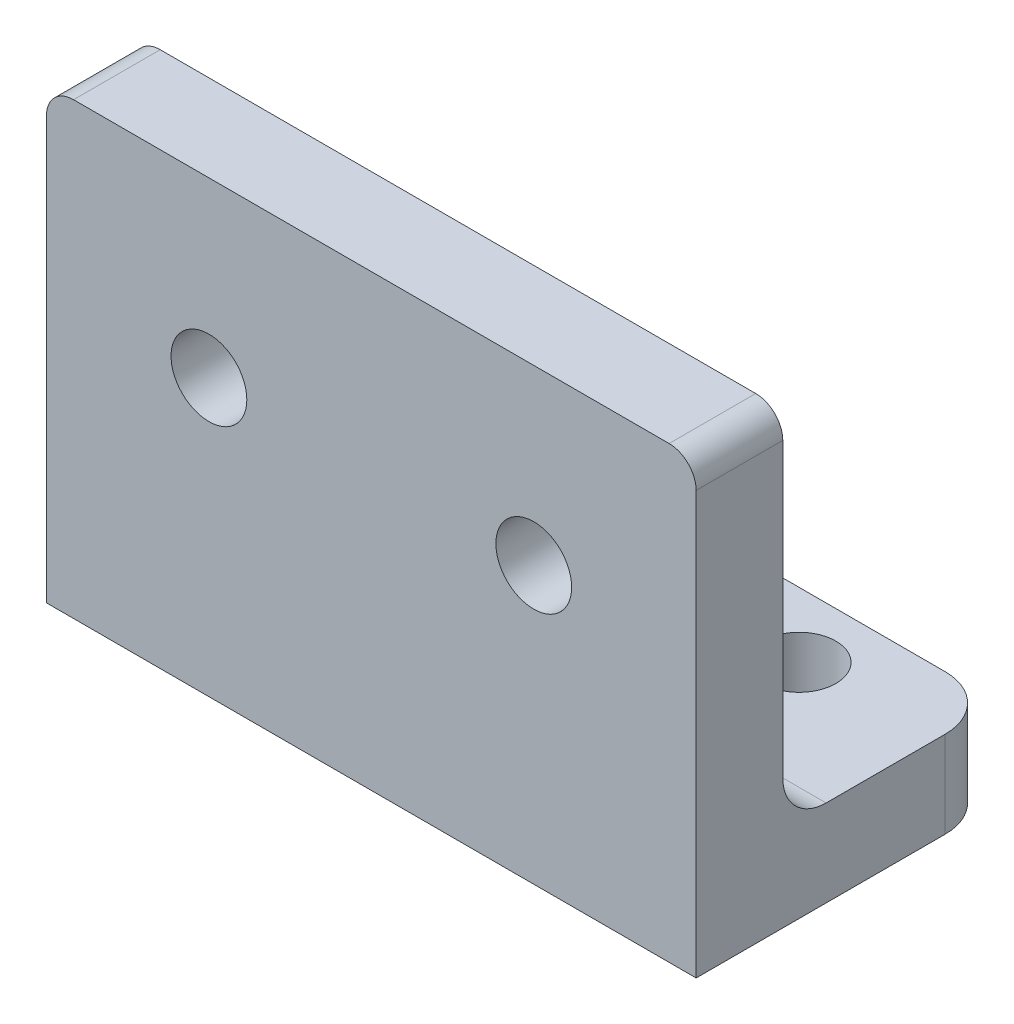
SolidWorks part; units mm, degrees
ref_plane "Front Plane" through (0, 0, 0) normal (0, 0, 1) x (1, 0, 0)
ref_plane "Top Plane" through (0, 0, 0) normal (0, 1, 0) x (1, 0, 0)
ref_plane "Right Plane" through (0, 0, 0) normal (1, 0, 0) x (0, 0, -1)
sketch "Sketch1" plane through (0, 0, 0) normal (0, 0, 1) x (1, 0, 0)
  line L1 (-15, 10.375) -> (15, 10.375)
  line L2 (-15, 10.375) -> (-15, -10.375)
  line L3 (-15, -10.375) -> (15, -10.375)
  line L4 (15, 10.375) -> (15, -10.375)
  line L5 (-15, 10.375) -> (15, -10.375) construction
  line L6 (-15, -10.375) -> (15, 10.375) construction
  point P0 (0, 0)
  dimension "D1" = 30
  dimension "D2" = 20.75
extrude "Boss-Extrude1" add sketch "Sketch1" along normal blind 4
fillet "Fillet1" radius 1.25 2 edges at (15, 10.375, 2) (-15, 10.375, 2)
sketch "Sketch3" plane through (0, 0, 4) normal (0, 0, 1) x (1, 0, 0)
  circle A0 centre (-7.5, 2.375) radius 1.75
  circle A1 centre (7.5, 2.375) radius 1.75
extrude "Cut-Extrude1" cut sketch "Sketch3" against normal blind 10
sketch "Sketch4" plane through (0, 0, 0) normal (0, 0, -1) x (-1, 0, 0)
  line L0 (15, 9.125) -> (15, -10.375) construction
  line L1 (-15, -10.375) -> (15, -10.375)
  line L2 (-15, -10.375) -> (-15, -6.375)
  line L3 (-15, -6.375) -> (15, -6.375)
  line L4 (15, -10.375) -> (15, -6.375)
  dimension "D1" = 4
extrude "Boss-Extrude2" add sketch "Sketch4" along normal blind 10
fillet "Fillet2" radius 2.5 2 edges at (15, -8.375, -10) (-15, -8.375, -10)
fillet "Fillet3" radius 2 1 edges at (0, -6.375, 0)
hole_wizard "M3 Clearance Hole1" positions "Sketch5" profile "Sketch6" hole size "M3" standard "ISO"
sketch "Sketch5" plane through (0, -10.375, 0) normal (0, -1, 0) x (-1, 0, 0)
  line L0 (-8.75, 10) -> (-8.75, 7) construction
  line L1 (-12.5, 10) -> (12.5, 10) construction
  line L5 (0, 0) -> (0, 10) construction
  line L7 (-8.75, 7) -> (0, 7) construction
  line L9 (0, 7) -> (8.75, 7) construction
  point P0 (-8.75, 7)
  point P2 (8.75, 7)
  dimension "D1" = 3
  dimension "D2" = 8.75
sketch "Sketch6" plane through (8.75, -10.375, -7) normal (1, 0, 0) x (0, 0, -1)
  line L0 (0, 0) -> (0, 17.0215)
  line L1 (0, 17.0215) -> (1.7, 16)
  line L2 (1.7, 16) -> (1.7, 0)
  line L5 (1.7, 0) -> (0, 0)
  line L10 (0, 17.0215) -> (-1.7, 16) construction
  line L11 (0, -6.35) -> (0, 107.95) construction
  dimension "Hole Dia." = 3.4
  dimension "Hole Depth" = 16
  dimension "Drill Angle" = 118
